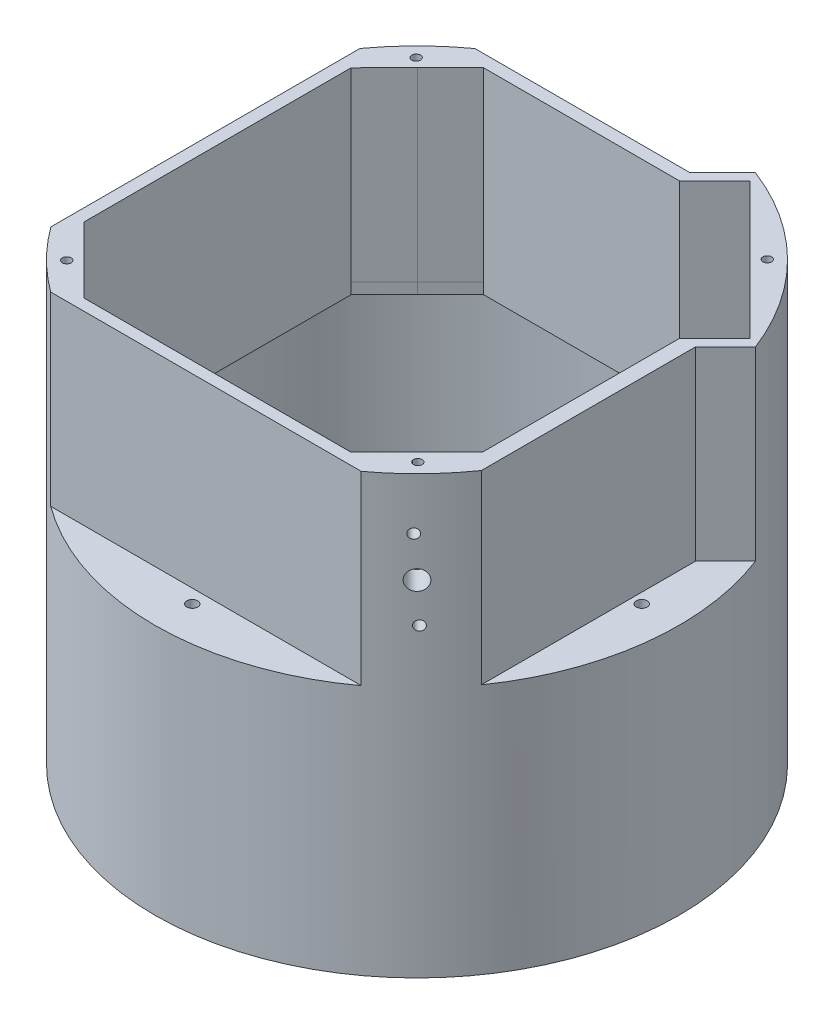
SolidWorks part; units mm, degrees
material "PE Alta densidad"
ref_plane "Alzado" through (0, 0, 0) normal (0, 0, 1) x (1, 0, 0)
ref_plane "Planta" through (0, 0, 0) normal (0, 1, 0) x (1, 0, 0)
ref_plane "Vista lateral" through (0, 0, 0) normal (1, 0, 0) x (0, 0, -1)
sketch "Croquis1" plane through (0, 0, 0) normal (0, 1, 0) x (1, 0, 0)
  circle A0 centre (0, 0) radius 115
  circle A1 centre (0, 0) radius 120
  dimension "D1" = 230
  dimension "D2" = 240
extrude "Saliente-Extruir1" add sketch "Croquis1" along normal blind 110
sketch "Croquis2" plane through (0, 110, 0) normal (0, 1, 0) x (1, 0, 0)
  line L1 (-76.1267, -76.2887) -> (76.1267, -76.2887)
  line L2 (-76.1267, -76.2887) -> (-76.1267, 76.2887)
  line L3 (-76.1267, 76.2887) -> (76.1267, 76.2887)
  line L4 (76.1267, -76.2887) -> (76.1267, 76.2887)
  line L5 (-76.1267, -76.2887) -> (76.1267, 76.2887) construction
  line L6 (-76.1267, 76.2887) -> (76.1267, -76.2887) construction
  circle A0 centre (0, 0) radius 120
  dimension "D1" = 240
extrude "Saliente-Extruir2" add sketch "Croquis2" along normal blind 90
sketch "Croquis3" plane through (0, 200, 0) normal (0, 1, 0) x (1, 0, 0)
  line L0 (0, 140.4757) -> (0, -145.6483) construction
  line L1 (-96.9086, 70.7723) -> (-133.113, 70.7723)
  line L2 (-96.9086, 70.7723) -> (-96.9086, -77.9079)
  line L3 (-96.9086, -77.9079) -> (-133.113, -77.9079)
  line L4 (-133.113, 70.7723) -> (-133.113, -77.9079)
  line L5 (-183.9307, 0) -> (147.8803, 0) construction
  line L6 (-76.1267, 76.2887) -> (-76.1267, -76.2887) construction
  line L7 (76.1267, -76.2887) -> (76.1267, 76.2887) construction
  line L13 (-71.1186, -96.6547) -> (78.7932, -96.6547)
  line L14 (-71.1186, -96.6547) -> (-71.1186, -128.557)
  line L15 (-71.1186, -128.557) -> (78.7932, -128.557)
  line L16 (78.7932, -96.6547) -> (78.7932, -128.557)
  line L20 (76.1267, -76.2887) -> (61.007, -91.4084)
  line L25 (61.007, -91.4084) -> (45.8874, -76.2887)
  line L26 (-76.1267, -76.2887) -> (76.1267, -76.2887) construction
  line L27 (76.1267, -76.2887) -> (91.2674, -61.148)
  line L28 (91.2674, -61.148) -> (76.1267, -46.0073)
  line L29 (76.1267, -46.0073) -> (45.8874, -76.2887)
  line L30 (-76.1267, 76.2887) -> (-61.005, 91.4314)
  line L31 (76.1267, 76.2887) -> (-76.1267, 76.2887) construction
  line L32 (-61.005, 91.4314) -> (-45.8412, 76.2887)
  line L33 (-45.8412, 76.2887) -> (-76.1267, 45.9611)
  line L34 (-76.1267, 76.2887) -> (-91.2674, 61.1018)
  line L35 (-91.2674, 61.1018) -> (-76.1267, 45.9611)
  line L36 (-76.1267, -76.2887) -> (-91.2674, -61.169)
  line L37 (-91.2674, -61.169) -> (-76.1267, -46.0073)
  line L38 (-76.1267, -46.0073) -> (-45.8873, -76.2887)
  line L39 (-45.8873, -76.2887) -> (-61.028, -91.4084)
  line L40 (-61.028, -91.4084) -> (-76.1267, -76.2887)
  line L46 (-91.2674, 61.1018) -> (-91.2674, -61.169)
  line L47 (-61.028, -91.4084) -> (61.007, -91.4084)
  line L48 (-61.005, 91.4314) -> (28.8072, 91.4314)
  line L49 (91.2674, 61.19) -> (61.007, 91.4084)
  line L50 (91.2674, -61.148) -> (91.2674, 28.9712)
  line L51 (-116.0104, 128.981) -> (27.7326, 128.981)
  line L52 (27.7326, 97.0786) -> (27.7326, 128.981)
  line L53 (-116.0104, 97.0786) -> (27.7326, 97.0786)
  line L54 (-116.0104, 97.0786) -> (-116.0104, 128.981)
  line L55 (98.3001, -119.3493) -> (134.5045, -119.3493)
  line L56 (134.5045, 29.3309) -> (134.5045, -119.3493)
  line L57 (98.3001, 29.3309) -> (134.5045, 29.3309)
  line L58 (98.3001, 29.3309) -> (98.3001, -119.3493)
  line L59 (98.3001, 29.3309) -> (112.014, 43.0448)
  line L60 (91.2674, 61.19) -> (107.3769, 45.0806)
  line L61 (107.3769, 45.0806) -> (91.2674, 28.9712)
  line L62 (91.2674, 28.9712) -> (28.8072, 91.4314)
  line L63 (27.7326, 97.0786) -> (42.7723, 112.1184)
  line L64 (28.8072, 91.4314) -> (44.8956, 107.5199)
  line L65 (61.007, 91.4084) -> (44.8956, 107.5199)
  circle A0 centre (0, 0) radius 120 construction
  arc A1 (42.7723, 112.1184) -> (112.014, 43.0448) centre (0, 0) cw
  circle M11 centre (0, 0) radius 120
  line M12 (-76.1267, 76.2887) -> (76.1267, 76.2887)
  line M13 (76.1267, 76.2887) -> (76.1267, -76.2887)
  line M14 (76.1267, -76.2887) -> (-76.1267, -76.2887)
  line M15 (-76.1267, -76.2887) -> (-76.1267, 76.2887)
extrude "Cortar-Extruir1" cut sketch "Croquis3" against normal blind 85 contours L62 L48 L32 M12 | L35 L46 L37 M15 | L39 L47 L25 M14 | L50 L62 L28 M13 | L57 L58 M11 | L13 M11 | L2 M11 | L53 L52 M11 | L49 L65 L64 L62 L61 L60 M12 M13 | L25 L20 M14 | L27 L28 M13 | L37 L36 M15 | L40 L39 M14 | L34 L35 M15 | L32 L30 M12 | L52 L63 M11 | L59 L57 M11
sketch "Croquis4" plane through (0, 115, 0) normal (0, 1, 0) x (1, 0, 0)
  line L1 (-91.2674, 61.1018) -> (-91.2674, -61.169)
  line L2 (-91.2674, -61.169) -> (-61.028, -91.4084)
  line L3 (-61.028, -91.4084) -> (61.007, -91.4084)
  line L4 (-91.2674, 61.1018) -> (-61.005, 91.4314)
  line L9 (-61.005, 91.4314) -> (28.8072, 91.4314)
  line L10 (28.8072, 91.4314) -> (44.8956, 107.5199)
  line L11 (44.8956, 107.5199) -> (107.3769, 45.0806)
  line L12 (107.3769, 45.0806) -> (91.2674, 28.9712)
  line L13 (91.2674, 28.9712) -> (91.2674, -61.148)
  line L14 (91.2674, -61.148) -> (61.007, -91.4084) construction
  line L15 (91.2674, -61.148) -> (91.2674, 28.9712) construction
  line L16 (91.2674, -61.148) -> (61.007, -91.4084)
extrude "Cortar-Extruir2" cut sketch "Croquis4" against normal blind 30
sketch "Croquis5" plane through (0, 200, 0) normal (0, 1, 0) x (1, 0, 0)
  circle A0 centre (80.0095, 80.4031) radius 2
  circle A1 centre (-80.4031, 80.0095) radius 2
  circle A2 centre (-80.0095, -80.4031) radius 2
  circle A3 centre (80.4031, -80.0095) radius 2
extrude "Cortar-Extruir3" cut sketch "Croquis5" against normal blind 10
sketch "Croquis7" plane through (76.2077, 0, 76.2077) normal (-0.7071, 0, -0.7071) x (-0.7071, 0, 0.7071)
  circle A0 centre (0, 157.8519) radius 4.5
  dimension "D1" = 9
extrude "Cortar-Extruir4" cut sketch "Croquis7" against normal through all
sketch "Croquis8" plane through (76.2077, 0, 76.2077) normal (-0.7071, 0, -0.7071) x (-0.7071, 0, 0.7071)
  circle A0 centre (1.0558, 176.2653) radius 2.25
  circle A1 centre (-0.7907, 139.8172) radius 2.25
  dimension "D1" = 4.5
  dimension "D2" = 4.5
extrude "Cortar-Extruir5" cut sketch "Croquis8" against normal blind 30
sketch "Croquis12" plane through (0, 115, 0) normal (0, 1, 0) x (1, 0, 0)
  circle A0 centre (102.9287, 0) radius 2.5
  circle A1 centre (0, -102.9287) radius 2.5
  circle A2 centre (-102.9287, 0) radius 2.5
  circle A3 centre (0, 102.9287) radius 2.5
  point P11 (0, 0)
  dimension "D1" = 5
  dimension "D2" = 4
extrude "Cortar-Extruir7" cut sketch "Croquis12" against normal blind 15
